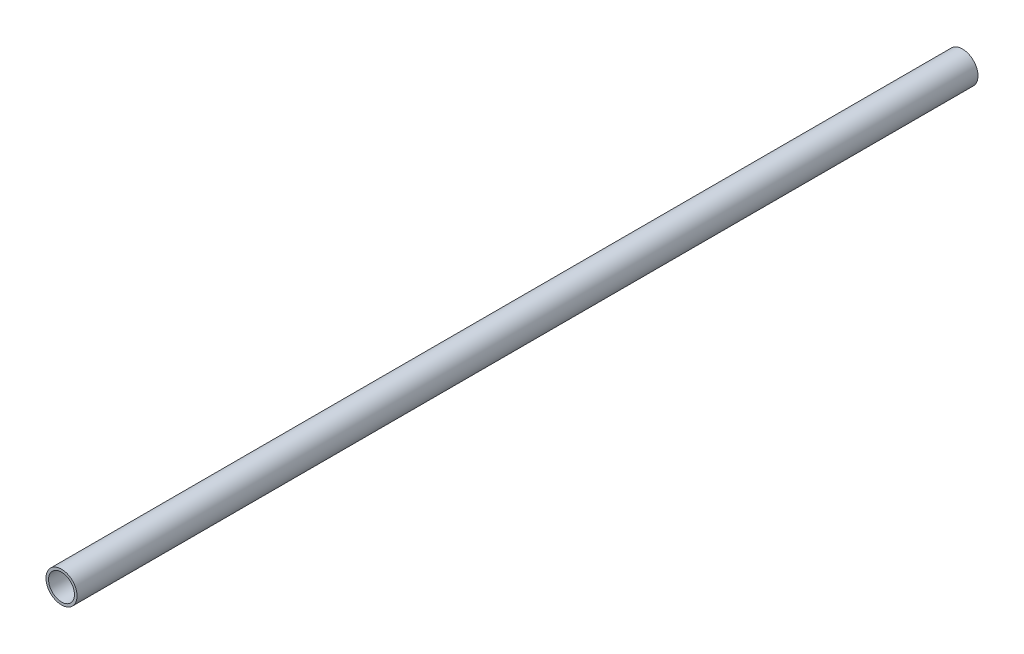
SolidWorks part; units mm, degrees
ref_plane "Front Plane" through (0, 0, 0) normal (0, 0, 1) x (1, 0, 0)
ref_plane "Top Plane" through (0, 0, 0) normal (0, 1, 0) x (1, 0, 0)
ref_plane "Right Plane" through (0, 0, 0) normal (1, 0, 0) x (0, 0, -1)
sketch "Sketch1" plane through (0, 0, 0) normal (0, 0, 1) x (1, 0, 0)
  circle A0 centre (0, 0) radius 6
  circle A1 centre (0, 0) radius 5
  dimension "D1" = 12
  dimension "D2" = 10
extrude "Boss-Extrude1" add sketch "Sketch1" along normal blind 347.94
